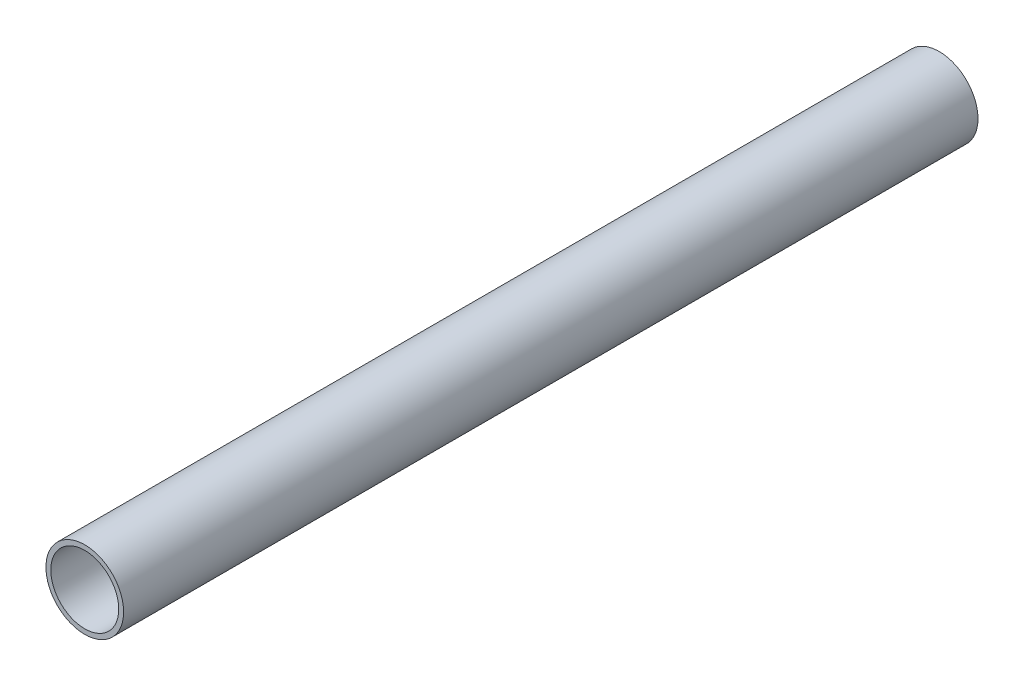
SolidWorks part; units mm, degrees
material "Hexcel AS4C (3000 Filaments)"
ref_plane "Front Plane" through (0, 0, 0) normal (0, 0, 1) x (1, 0, 0)
ref_plane "Top Plane" through (0, 0, 0) normal (0, 1, 0) x (1, 0, 0)
ref_plane "Right Plane" through (0, 0, 0) normal (1, 0, 0) x (0, 0, -1)
sketch "Sketch1" plane through (0, 0, 0) normal (0, 0, 1) x (1, 0, 0)
  circle A0 centre (0, 0) radius 12.7
  circle A1 centre (0, 0) radius 11.1125
  dimension "D1" = 25.4
  dimension "D2" = 22.225
extrude "Boss-Extrude1" add sketch "Sketch1" along normal blind 279.4
